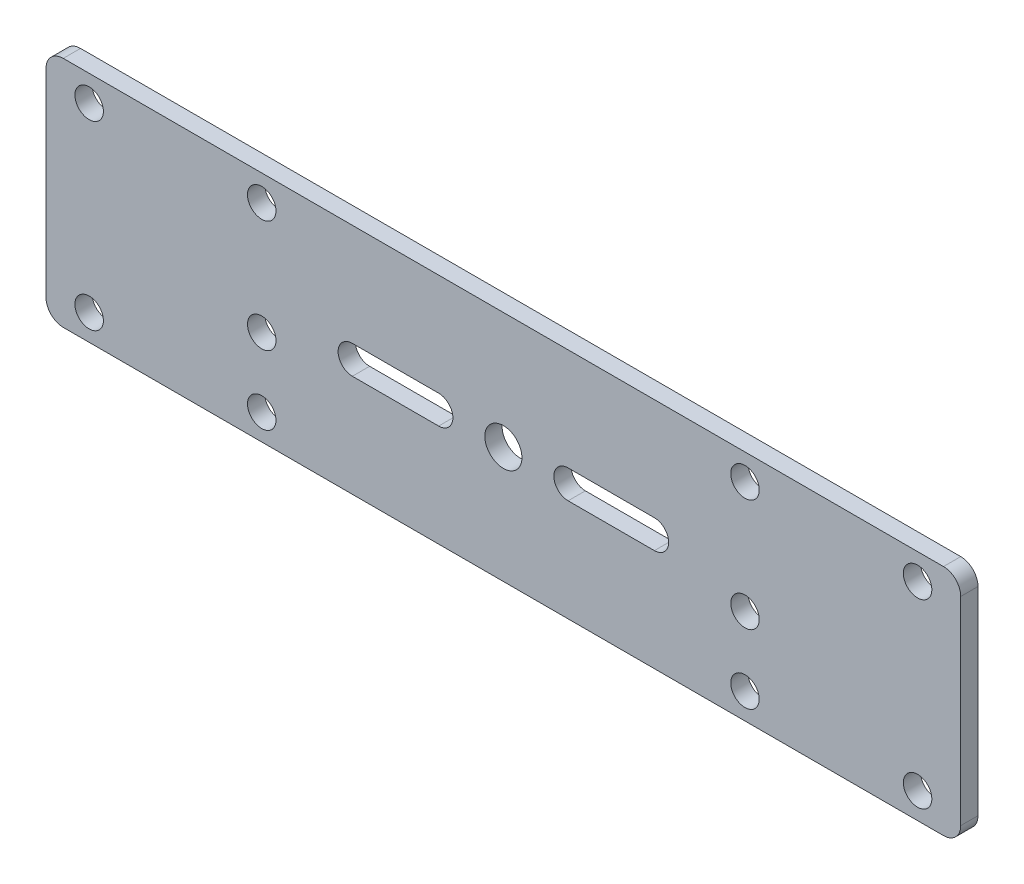
SolidWorks part; units mm, degrees
material "环氧板"
ref_plane "前视基准面" through (0, 0, 0) normal (0, 0, 1) x (1, 0, 0)
ref_plane "上视基准面" through (0, 0, 0) normal (0, 1, 0) x (1, 0, 0)
ref_plane "右视基准面" through (0, 0, 0) normal (1, 0, 0) x (0, 0, -1)
other "Configuration Table"
sketch "草图1" plane through (0, 0, 0) normal (0, 0, 1) x (1, 0, 0)
  line L0 (0, 12.5) -> (0, -24.1322) construction
  line L1 (-53, 12.5) -> (53, 12.5)
  line L2 (-53, 12.5) -> (-53, -12.5)
  line L3 (-53, -12.5) -> (53, -12.5)
  line L4 (53, 12.5) -> (53, -12.5)
  line L5 (-53, 12.5) -> (53, -12.5) construction
  line L6 (-53, -12.5) -> (53, 12.5) construction
  line L7 (0, -1) -> (-43.9119, -1) construction
  circle A0 centre (-28, 5.5) radius 1.65
  circle A1 centre (-28, -7.5) radius 1.65
  circle A2 centre (28, -7.5) radius 1.65
  circle A3 centre (28, 5.5) radius 1.65
  circle A4 centre (0, 5.5) radius 1.65 construction
  circle A5 centre (0, -7.5) radius 1.65 construction
  circle A6 centre (-48, 5.5) radius 1.65
  circle A7 centre (48, 5.5) radius 1.65
  circle A8 centre (0, -5) radius 2.15
  point P0 (0, 0)
  dimension "D2" = 3.3
  dimension "D3" = 13
  dimension "D4" = 56
  dimension "D7" = 20
  dimension "D8" = 17.5
  dimension "D9" = 4.3
  dimension "D1" = 25
  dimension "D5" = 106
  dimension "D6" = 1
extrude "凸台-拉伸1" add sketch "草图1" along normal blind 2
sketch "草图2" plane through (0, 0, 2) normal (0, 0, 1) x (1, 0, 0)
  line L1 (-53, -12.5) -> (53, -12.5)
  line L2 (-53, -12.5) -> (-53, -18.5)
  line L3 (-53, -18.5) -> (53, -18.5)
  line L4 (53, -12.5) -> (53, -18.5)
  dimension "D1" = 6
extrude "凸台-拉伸3" add sketch "草图2" against normal blind 2
sketch "草图4" plane through (0, 0, 2) normal (0, 0, 1) x (1, 0, 0)
  line L0 (0, 0) -> (0, -31.5427) construction
  circle A0 centre (-48, -15.5) radius 1.65
  circle A1 centre (-48, 5.5) radius 1.65 construction
  circle A2 centre (-48, 5.5) radius 1.65 construction
  circle A3 centre (48, -15.5) radius 1.65
  circle A4 centre (-28, -15.5) radius 1.65
  circle A5 centre (28, -15.5) radius 1.65
  dimension "D1" = 21
  dimension "D2" = 20
extrude "切除-拉伸1" cut sketch "草图4" against normal through all
sketch "草图5" plane through (0, 0, 2) normal (0, 0, 1) x (1, 0, 0)
  line L0 (-17.5, -5) -> (-7.5, -5) construction
  line L1 (-17.5, -3.35) -> (-7.5, -3.35)
  line L2 (-17.5, -6.65) -> (-7.5, -6.65)
  line L3 (0, 0) -> (0, 32.804) construction
  line L4 (17.5, -5) -> (7.5, -5) construction
  line L5 (17.5, -3.35) -> (7.5, -3.35)
  line L6 (17.5, -6.65) -> (7.5, -6.65)
  arc A0 (-17.5, -3.35) -> (-17.5, -6.65) centre (-17.5, -5) ccw
  arc A1 (-7.5, -6.65) -> (-7.5, -3.35) centre (-7.5, -5) ccw
  circle A2 centre (0, -5) radius 2.15 construction
  circle A3 centre (0, -5) radius 2.15 construction
  arc A4 (17.5, -3.35) -> (17.5, -6.65) centre (17.5, -5) cw
  arc A5 (7.5, -6.65) -> (7.5, -3.35) centre (7.5, -5) cw
  point P2 (-12.5, -5)
  point P15 (12.5, -5)
  dimension "D1" = 1.65
  dimension "D2" = 25
  dimension "D3" = 10
extrude "切除-拉伸2" cut sketch "草图5" against normal blind 10
sketch "草图6" plane through (0, 0, 2) normal (0, 0, 1) x (1, 0, 0)
  line L0 (53, -18.5) -> (53, 12.5) construction
  line L1 (-53, 12.5) -> (53, 12.5)
  line L2 (-53, 12.5) -> (-53, 8.5)
  line L3 (-53, 8.5) -> (53, 8.5)
  line L4 (53, 12.5) -> (53, 8.5)
  circle A0 centre (48, 5.5) radius 1.65 construction
  dimension "D1" = 3
extrude "切除-拉伸3" cut sketch "草图6" against normal through all
fillet "圆角1" radius 2 4 edges at (53, 8.5, 1) (53, -18.5, 1) (-53, -18.5, 1) (-53, 8.5, 1)
